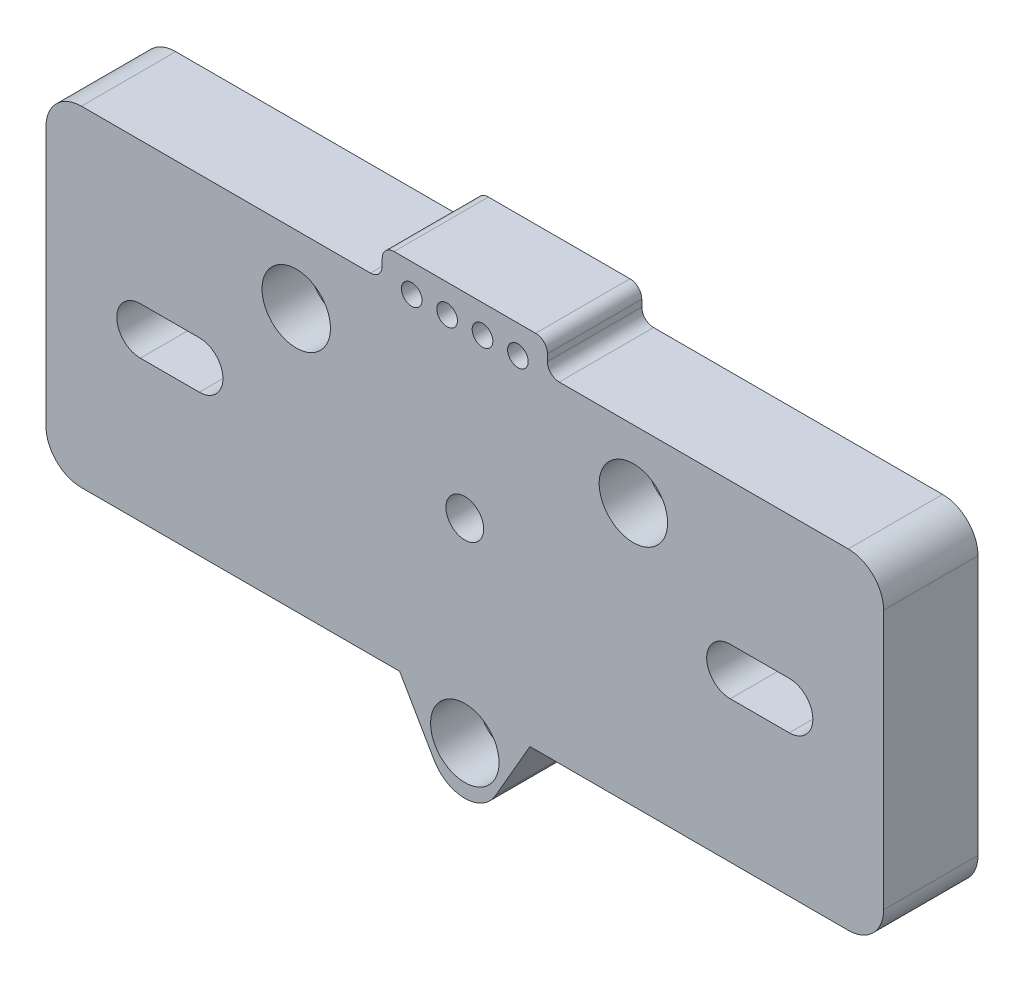
SolidWorks part; units mm, degrees
material "Bakelite"
ref_plane "Front Plane" through (0, 0, 0) normal (0, 0, 1) x (1, 0, 0)
ref_plane "Top Plane" through (0, 0, 0) normal (0, 1, 0) x (1, 0, 0)
ref_plane "Right Plane" through (0, 0, 0) normal (1, 0, 0) x (0, 0, -1)
sketch "Model" plane through (0, 0, 0) normal (0, 0, 1) x (1, 0, 0)
  line L0 (20.4053, 11.78) -> (-20.4053, 11.78)
  line L2 (0, -23.5631) -> (20.4053, 11.78)
  line L3 (-20.4053, 11.78) -> (0, -23.5631)
  circle A0 centre (0, -16.5) radius 1.75
  circle A1 centre (0, 0) radius 1.6
  circle A2 centre (-14.2894, 8.25) radius 1.75
  circle A3 centre (14.2894, 8.25) radius 1.75
  dimension "D1" = 3.2
  dimension "D2" = 3.5
  dimension "D3" = 11.7815
  dimension "D4" = 11.7815
  dimension "D5" = 11.78
  dimension "D6" = 60
  dimension "D13" = 16.5
extrude "Boss-Extrude1" add sketch "Model" along normal blind 8
fillet "Fillet1" radius 3 3 edges at (0, -23.5631, 4) (-20.4053, 11.78, 4) (20.4053, 11.78, 4)
sketch "Sketch1" plane through (0, 0, 0) normal (0, 0, -1) x (-1, 0, 0)
  line L0 (-7, 16.58) -> (-7, 14)
  line L1 (-15.2092, 11.78) -> (15.2092, 11.78) construction
  line L2 (-7, 16.58) -> (7, 16.58)
  line L3 (7, 16.58) -> (7, 14)
  line L4 (-4.5, 14.18) -> (4.5, 14.18) construction
  line L5 (0, 16.58) -> (0, 11.78) construction
  line L6 (-5.5212, -14) -> (5.5212, -14)
  line L7 (-35.5, 14) -> (-7, 14)
  line L8 (-35.5, 14) -> (-35.5, -14)
  line L9 (-35.5, -14) -> (-5.5212, -14)
  line L11 (-2.5981, -19.0631) -> (-17.8072, 7.28) construction
  line L12 (7, 14) -> (35.5, 14)
  line L13 (35.5, 14) -> (35.5, -14)
  line L14 (35.5, -14) -> (5.5212, -14)
  line L15 (17.8072, 7.28) -> (2.5981, -19.0631) construction
  line L20 (-27.5, 0) -> (-22.5, 0) construction
  line L21 (-27.5, 2) -> (-22.5, 2)
  line L22 (-27.5, -2) -> (-22.5, -2)
  line L23 (22.5, 0) -> (27.5, 0) construction
  line L24 (22.5, 2) -> (27.5, 2)
  line L25 (22.5, -2) -> (27.5, -2)
  line L26 (0, 0) -> (0, 6.3594) construction
  line L27 (-25, 0) -> (0, 0) construction
  circle A0 centre (-1.5, 14.18) radius 0.875
  circle A1 centre (-4.5, 14.18) radius 0.875
  circle A2 centre (1.5, 14.18) radius 0.875
  circle A3 centre (4.5, 14.18) radius 0.875
  arc A5 (-27.5, 2) -> (-27.5, -2) centre (-27.5, 0) ccw
  arc A6 (-22.5, -2) -> (-22.5, 2) centre (-22.5, 0) ccw
  arc A7 (22.5, 2) -> (22.5, -2) centre (22.5, 0) ccw
  arc A8 (27.5, -2) -> (27.5, 2) centre (27.5, 0) ccw
  circle A9 centre (-14.2894, 8.25) radius 1.75
  circle A10 centre (14.2894, 8.25) radius 1.75
  circle A11 centre (0, 0) radius 1.6
  point P4 (0, 11.78)
  point P7 (0, 11.78)
  point P43 (-25, 0)
  point P48 (25, 0)
  dimension "D3" = 1.75
  dimension "D7" = 35.5
  dimension "D10" = 2
  dimension "D11" = 5
  dimension "D1" = 14
  dimension "D2" = 2.4
  dimension "D4" = 3
  dimension "D5" = 3
  dimension "D6" = 3
  dimension "D8" = 35.5
  dimension "D9" = 28
  dimension "D12" = 50
  dimension "D14" = 5
extrude "Boss-Extrude2" add sketch "Sketch1" against normal up to surface (8 mm away) up to face at (-12.5394, 8.25, 8)
fillet "Fillet2" radius 1 4 edges at (-7, 14, 4) (-7, 16.58, 4) (7, 16.58, 4) (7, 14, 4)
fillet "Fillet3" radius 3 4 edges at (35.5, -14, 4) (-35.5, -14, 4) (-35.5, 14, 4) (35.5, 14, 4)
sketch "Sketch2" plane through (0, 0, 8) normal (0, 0, 1) x (1, 0, 0)
  circle A0 centre (-14.2894, 8.25) radius 2.9
  circle A2 centre (14.2894, 8.25) radius 2.9
  circle A3 centre (0, -16.5) radius 2.9
  dimension "D1" = 5.8
extrude "Cut-Extrude1" cut sketch "Sketch2" against normal blind 4
chamfer "Chamfer1" distance 1 angle 45 4 edges at (1.75, -16.5, 0) (-12.5394, 8.25, 0) (16.0394, 8.25, 0) (1.6, 0, 0)
